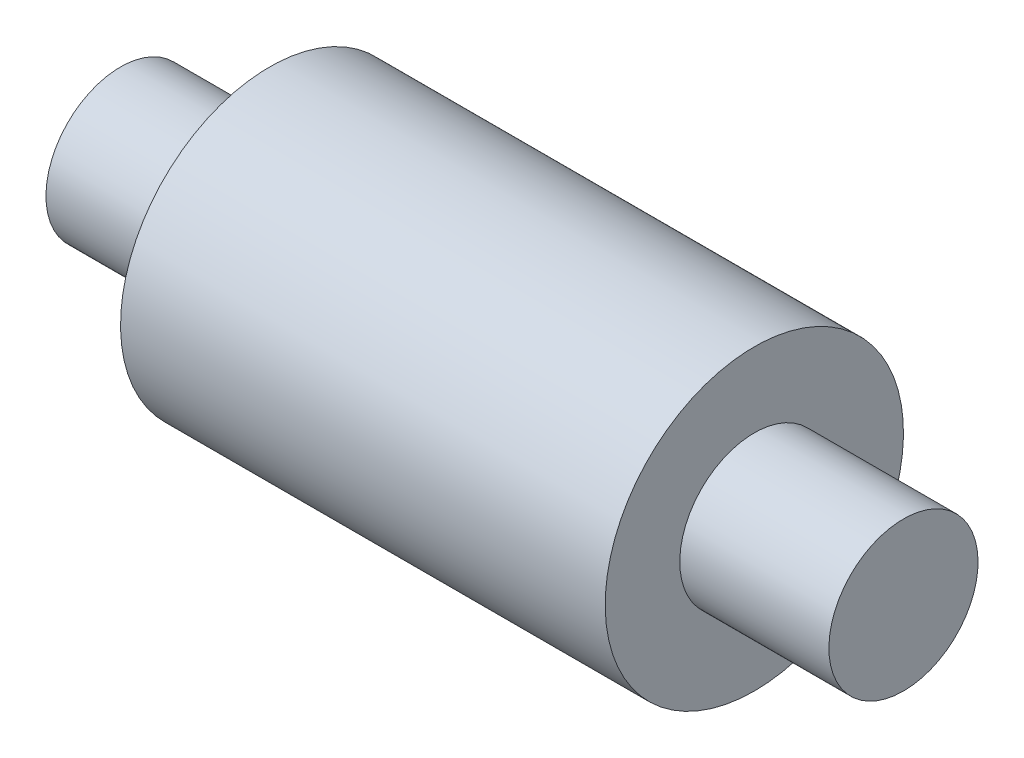
SolidWorks part; units mm, degrees
ref_plane "前视基准面" through (0, 0, 0) normal (0, 0, 1) x (1, 0, 0)
ref_plane "上视基准面" through (0, 0, 0) normal (0, 1, 0) x (1, 0, 0)
ref_plane "右视基准面" through (0, 0, 0) normal (1, 0, 0) x (0, 0, -1)
sketch "草图1" plane through (0, 0, 0) normal (0, 0, 1) x (1, 0, 0)
  line L0 (-16.7018, 0) -> (17, 0)
  line L1 (0, 0) -> (0, 2)
  line L2 (0, 2) -> (4, 2)
  line L3 (4, 2) -> (4, 4)
  line L4 (4, 4) -> (17, 4)
  line L5 (17, 4) -> (17, 2)
  line L6 (17, 2) -> (21, 2)
  line L7 (21, 2) -> (21, 0)
  line L8 (21, 0) -> (17, 0)
  dimension "D1" = 2
  dimension "D2" = 2
  dimension "D3" = 4
  dimension "D4" = 13
  dimension "D5" = 4
  dimension "D6" = 4
revolve "旋转2" add sketch "草图1" angle 360 about L0
sketch "草图2" plane through (0, 0, 0) normal (0, 1, 0) x (1, 0, 0)
  line L0 (0, 0) -> (21, 0)
  line L1 (21, -2) -> (21, 2) construction
  circle A0 centre (10.5, 0) radius 1
  dimension "D1" = 2
extrude "切除-拉伸1" cut sketch "草图2" against normal blind 30 contours L0 A0
